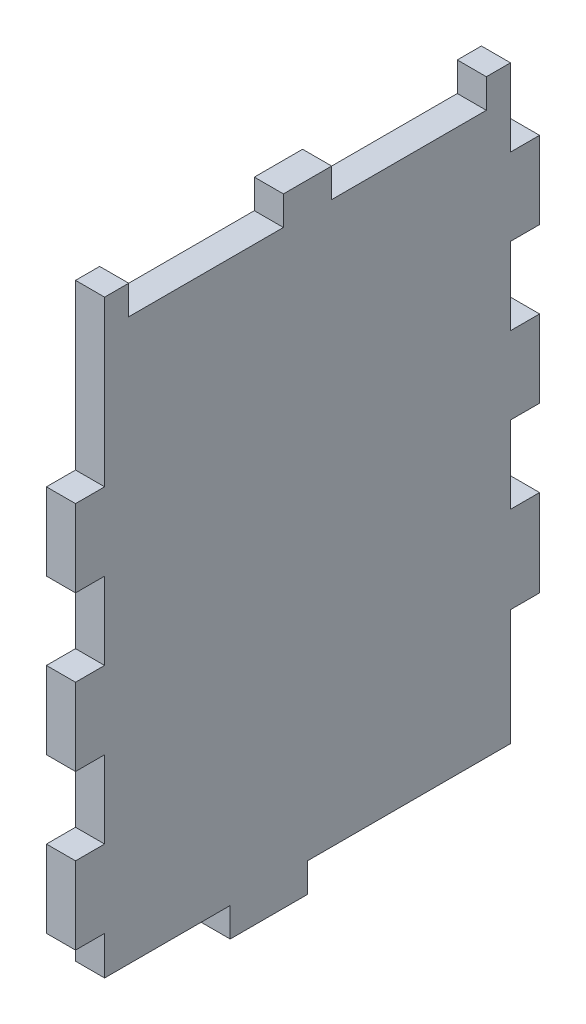
SolidWorks part; units mm, degrees
ref_plane "Front Plane" through (0, 0, 0) normal (0, 0, 1) x (1, 0, 0)
ref_plane "Top Plane" through (0, 0, 0) normal (0, 1, 0) x (1, 0, 0)
ref_plane "Right Plane" through (0, 0, 0) normal (1, 0, 0) x (0, 0, -1)
sketch "Sketch2" plane through (0, 0, 0) normal (1, 0, 0) x (0, 0, -1)
  line L1 (0, 0) -> (76.2, 0)
  line L2 (0, 0) -> (0, 101.6)
  line L3 (0, 101.6) -> (76.2, 101.6)
  line L4 (76.2, 0) -> (76.2, 101.6)
  dimension "D1" = 76.2
  dimension "D2" = 101.6
extrude "Boss-Extrude1" add sketch "Sketch2" along normal blind 4.7752
sketch "Sketch3" plane through (4.7752, 0, 0) normal (1, 0, 0) x (0, 0, -1)
  line L0 (0, 0) -> (76.2, 0) construction
  line L1 (0, 0) -> (25.4, 0)
  line L2 (0, 0) -> (0, 4.7752)
  line L3 (0, 4.7752) -> (25.4, 4.7752)
  line L4 (25.4, 0) -> (25.4, 4.7752)
  line L6 (38.1, 0) -> (25.4, 0)
  line L7 (38.1, 0) -> (38.1, 4.7752)
  line L8 (38.1, 4.7752) -> (25.4, 4.7752)
  line L9 (25.4, 0) -> (25.4, 4.7752)
  line L10 (38.1, 4.7752) -> (76.2, 4.7752)
  line L11 (38.1, 4.7752) -> (38.1, 0)
  line L12 (38.1, 0) -> (76.2, 0)
  line L13 (76.2, 4.7752) -> (76.2, 0)
  line M7 (0, 101.6) -> (0, 0)
  line M8 (0, 0) -> (76.2, 0)
  line M9 (76.2, 0) -> (76.2, 101.6)
  dimension "D1" = 25.4
  dimension "D2" = 4.7752
extrude "Cut-Extrude1" cut sketch "Sketch3" against normal blind 6.35 contours L4 L3 M8 M7 | L10 L7 M8 M9
sketch "Sketch4" plane through (4.7752, 0, 0) normal (1, 0, 0) x (0, 0, -1)
  line L0 (0, 11.1252) -> (0, 23.8252)
  line L1 (0, 4.7752) -> (4.7752, 4.7752)
  line L2 (0, 4.7752) -> (0, 11.1252)
  line L3 (0, 11.1252) -> (4.7752, 11.1252)
  line L4 (4.7752, 4.7752) -> (4.7752, 11.1252)
  line L5 (0, 101.6) -> (0, 4.7752) construction
  line L6 (76.2, 4.7752) -> (76.2, 101.6) construction
  line L7 (0, 23.8252) -> (4.7752, 23.8252)
  line L8 (0, 23.8252) -> (0, 36.5252)
  line L9 (0, 36.5252) -> (4.7752, 36.5252)
  line L10 (4.7752, 23.8252) -> (4.7752, 36.5252)
  line L11 (0, 49.2252) -> (4.7752, 49.2252)
  line L12 (0, 49.2252) -> (0, 61.9252)
  line L13 (0, 61.9252) -> (4.7752, 61.9252)
  line L14 (4.7752, 49.2252) -> (4.7752, 61.9252)
  line L15 (0, 101.6) -> (4.7752, 101.6)
  line L16 (0, 101.6) -> (0, 74.6252)
  line L17 (0, 74.6252) -> (4.7752, 74.6252)
  line L18 (4.7752, 101.6) -> (4.7752, 74.6252)
  line L19 (76.2, 101.6) -> (71.4248, 101.6)
  line L20 (76.2, 101.6) -> (76.2, 88.9)
  line L21 (76.2, 88.9) -> (71.4248, 88.9)
  line L22 (71.4248, 101.6) -> (71.4248, 88.9)
  line L23 (76.2, 76.2) -> (71.4248, 76.2)
  line L24 (76.2, 76.2) -> (76.2, 63.5)
  line L25 (76.2, 63.5) -> (71.4248, 63.5)
  line L26 (71.4248, 76.2) -> (71.4248, 63.5)
  line L27 (38.1, 4.7752) -> (76.2, 4.7752) construction
  line L28 (71.4248, 50.8) -> (76.2, 50.8)
  line L29 (71.4248, 50.8) -> (71.4248, 38.1)
  line L30 (71.4248, 38.1) -> (76.2, 38.1)
  line L31 (76.2, 50.8) -> (76.2, 38.1)
  line L32 (71.4248, 23.8252) -> (76.2, 23.8252)
  line L33 (71.4248, 23.8252) -> (71.4248, 4.7752)
  line L34 (71.4248, 4.7752) -> (76.2, 4.7752)
  line L35 (76.2, 23.8252) -> (76.2, 4.7752)
  point P39 (70.1188, 6.35)
  point P42 (0, 74.6252)
  point P43 (0, 0)
  point P44 (4.7752, 74.6252)
  line M12 (0, 4.7752) -> (25.4, 4.7752)
  line M16 (38.1, 4.7752) -> (76.2, 4.7752)
  line M17 (76.2, 4.7752) -> (76.2, 101.6)
  line M18 (76.2, 101.6) -> (0, 101.6)
  line M19 (0, 101.6) -> (0, 4.7752)
  dimension "D1" = 6.35
  dimension "D2" = 4.7752
  dimension "D3" = 12.7
  dimension "D4" = 12.7
  dimension "D5" = 12.7
  dimension "D6" = 12.7
  dimension "D7" = 12.7
  dimension "D8" = 12.7
  dimension "D9" = 4.7752
  dimension "D10" = 19.05
  dimension "D11" = 4.7752
  dimension "D12" = 4.7752
  dimension "D13" = 12.7
  dimension "D14" = 12.7
  dimension "D15" = 4.7752
  dimension "D16" = 4.7752
  dimension "D17" = 4.7752
  dimension "D18" = 4.7752
extrude "Cut-Extrude2" cut sketch "Sketch4" against normal blind 6.35 contours L18 L17 M18 M19 | L22 L21 M18 M17 | L23 L26 L25 M17 | L4 L3 M12 M19 | L32 L33 M16 M17 | L29 L30 L28 M17 | L12 L13 L14 L11 | L8 L9 L10 L7
sketch "Sketch6" plane through (4.7752, 0, 0) normal (1, 0, 0) x (0, 0, -1)
  line L0 (38.1, 101.6) -> (4.7752, 101.6)
  line L1 (71.4248, 101.6) -> (4.7752, 101.6) construction
  line L2 (4.7752, 101.6) -> (4.7752, 96.8246)
  line L3 (4.7752, 96.8246) -> (71.4248, 96.8246)
  line L4 (71.4248, 101.6) -> (71.4248, 88.9) construction
  line L5 (71.4248, 96.8246) -> (71.4248, 101.6)
  line L6 (71.4248, 101.6) -> (38.1, 101.6)
  line L7 (21.4376, 101.6) -> (21.4376, 96.8246)
  line L9 (54.7624, 101.6) -> (54.7624, 96.8246)
  line L12 (8.7376, 96.8246) -> (34.1376, 96.8246)
  line L13 (8.7376, 96.8246) -> (8.7376, 101.6)
  line L14 (8.7376, 101.6) -> (34.1376, 101.6)
  line L15 (34.1376, 96.8246) -> (34.1376, 101.6)
  line L18 (67.4624, 96.8246) -> (42.0624, 96.8246)
  line L19 (67.4624, 96.8246) -> (67.4624, 101.6)
  line L20 (67.4624, 101.6) -> (42.0624, 101.6)
  line L21 (42.0624, 96.8246) -> (42.0624, 101.6)
  point P13 (21.4376, 99.2123)
  point P20 (54.7624, 99.2123)
  dimension "D1" = 25.4
  dimension "D2" = 25.4
extrude "Cut-Extrude4" cut sketch "Sketch6" against normal blind 4.7752 contours L3 L15 L0 L7 | L13 L3 L7 L0 | L21 L3 L9 L6 | L3 L19 L6 L9
